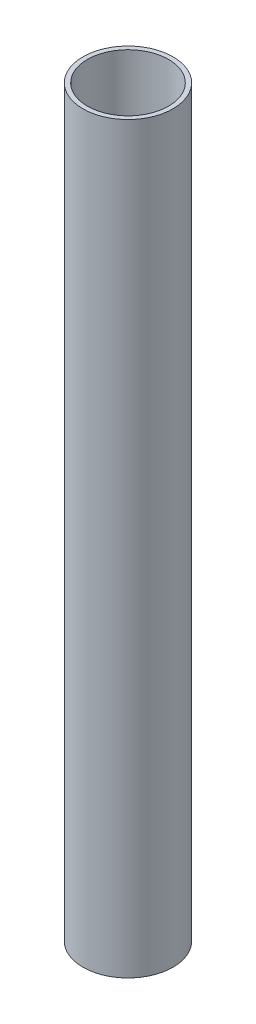
SolidWorks part; units mm, degrees
material "PMMA"
ref_plane "Alzado" through (0, 0, 0) normal (0, 0, 1) x (1, 0, 0)
ref_plane "Planta" through (0, 0, 0) normal (0, 1, 0) x (1, 0, 0)
ref_plane "Vista lateral" through (0, 0, 0) normal (1, 0, 0) x (0, 0, -1)
sketch "Croquis1" plane through (0, 0, 0) normal (0, 1, 0) x (1, 0, 0)
  circle A0 centre (0, 0) radius 20
  circle A1 centre (0, 0) radius 18
  dimension "D1" = 40
  dimension "D2" = 2
extrude "Saliente-Extruir1" add sketch "Croquis1" along normal blind 330
